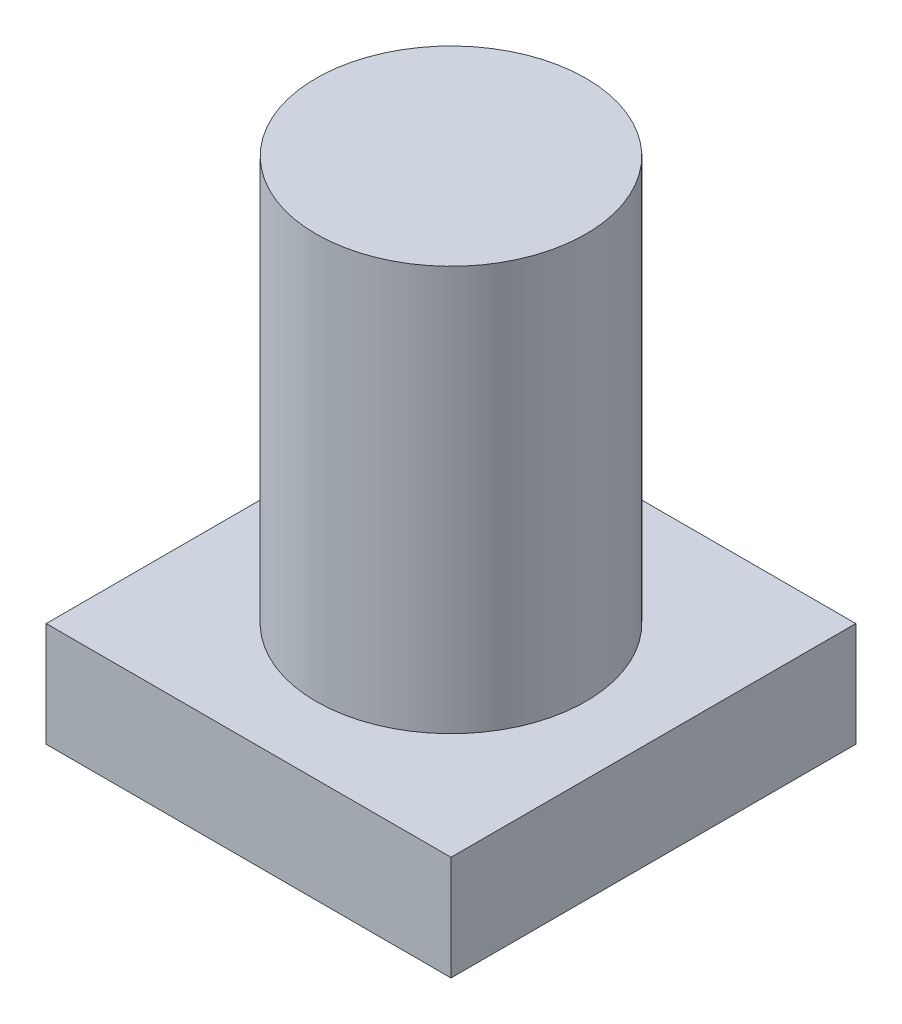
SolidWorks part; units mm, degrees
ref_plane "前视" through (0, 0, 0) normal (0, 0, 1) x (1, 0, 0)
ref_plane "上视" through (0, 0, 0) normal (0, 1, 0) x (1, 0, 0)
ref_plane "右视" through (0, 0, 0) normal (1, 0, 0) x (0, 0, -1)
sketch "草图1" plane through (0, 0, 0) normal (0, 1, 0) x (1, 0, 0)
  line L0 (0, 96.9306) -> (0, -101.3275) construction
  line L1 (-119.7143, 0) -> (134.9034, 0) construction
  line L3 (-6, 6) -> (6, 6)
  line L4 (-6, 6) -> (-6, -6)
  line L5 (-6, -6) -> (6, -6)
  line L6 (6, 6) -> (6, -6)
  dimension "D1" = 12
  dimension "D2" = 12
extrude "拉伸1" add sketch "草图1" along normal blind 3.1
sketch "草图2" plane through (0, 3.1, 0) normal (0, 1, 0) x (-1, 0, 0)
  line L0 (-6, 0) -> (8.7109, 0) construction
  line L1 (-6, 6) -> (-6, -6) construction
  line L2 (0, -7.8518) -> (0, 10.0992) construction
  circle A0 centre (0, 0) radius 4
  dimension "D1" = 8
extrude "拉伸2" add sketch "草图2" along normal blind 12
sketch "草图3" plane through (-6, 0, 0) normal (-1, 0, 0) x (0, 0, 1)
  line L0 (0, -6.9925) -> (0, 14.8526) construction
sketch "草图4" plane through (0, 15.1, 0) normal (0, 1, 0) x (-1, 0, 0)
  line L0 (0, -4.1469) -> (0, 4.9476) construction
  line L1 (-3.9082, 0) -> (5.1305, 0) construction
sketch "草图5" plane through (0, 0, 0) normal (0, -1, 0) x (1, 0, 0)
  line L0 (10.1949, 0) -> (-13.2034, 0) construction
  line L1 (0, 8.665) -> (0, -9.2576) construction
